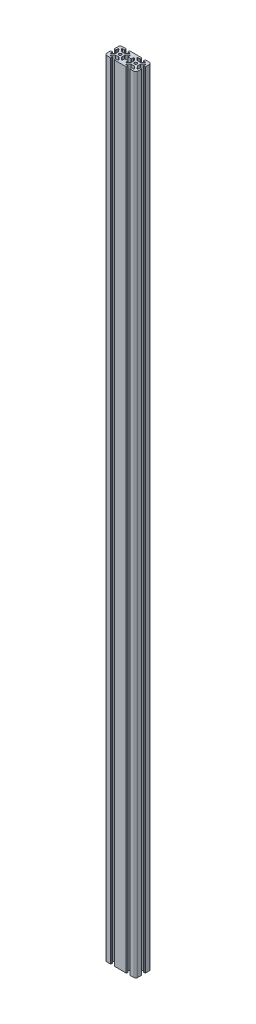
SolidWorks part; units mm, degrees
material "4032-T6"
ref_plane "Front Plane" through (0, 0, 0) normal (0, 0, 1) x (1, 0, 0)
ref_plane "Top Plane" through (0, 0, 0) normal (0, 1, 0) x (1, 0, 0)
ref_plane "Right Plane" through (0, 0, 0) normal (1, 0, 0) x (0, 0, -1)
sketch "Sketch1" plane through (0, 0, 0) normal (0, 1, 0) x (1, 0, 0)
  line L1 (5, 0) -> (75, 0)
  line L2 (0, -5) -> (0, -35)
  line L3 (5, -40) -> (75, -40)
  line L4 (80, -5) -> (80, -35)
  arc A0 (75, -40) -> (80, -35) centre (75, -35) ccw
  arc A1 (80, -5) -> (75, 0) centre (75, -5) ccw
  arc A2 (5, -40) -> (0, -35) centre (5, -35) cw
  arc A3 (0, -5) -> (5, 0) centre (5, -5) cw
  point P7 (80, -40)
  point P10 (80, 0)
  point P15 (0, 0)
  dimension "D3" = 5
  dimension "D1" = 80
  dimension "D2" = 40
extrude "Boss-Extrude1" add sketch "Sketch1" along normal blind 2016 contours L3 A0 L4 A1 L1 A3 L2 A2
sketch "Sketch3" plane through (0, 2016, 0) normal (0, 1, 0) x (1, 0, 0)
  line L0 (40, -2.5254) -> (40, -32.3671)
  line L1 (0, -5) -> (0, -35) construction
  line L2 (5, 0) -> (75, 0) construction
  circle A0 centre (20, -20) radius 3.4
  dimension "D4" = 6.8
  dimension "D1" = 40
  dimension "D2" = 20
  dimension "D3" = 20
extrude "Cut-Extrude1" cut sketch "Sketch3" against normal through all contours A0
ref_plane "mirro-plane" through (40, 0, 0) normal (1, 0, 0) x (0, 0, -1)
mirror "Mirror3" about plane through (40, 0, 0) normal (1, 0, 0) of "Cut-Extrude1"
ref_plane "sk5mirrorPlane" through (0, 0, 20) normal (0, 0, 1) x (1, 0, 0)
sketch "Sketch7" plane through (0, 0, 0) normal (0, -1, 0) x (-1, 0, 0)
  line L2 (-5, -40) -> (-75, -40) construction
  line L4 (-15.9, -40) -> (-24.1, -40)
  line L8 (-15.9, -40) -> (-15.9, -36.5)
  line L12 (-16.3092, -27.8) -> (-23.6908, -27.8)
  line L23 (-10.5103, -35.5) -> (-14.9, -35.5)
  line L25 (-24.1, -40) -> (-24.1, -36.5)
  line L27 (-15.6082, -28.0868) -> (-9.8093, -33.7868)
  line L31 (-29.4898, -35.5) -> (-25.1, -35.5)
  line L43 (-24.3918, -28.0868) -> (-30.1908, -33.7868)
  arc A0 (-24.3918, -28.0868) -> (-23.6908, -27.8) centre (-23.6908, -28.8) cw
  arc A1 (-16.3092, -27.8) -> (-15.6082, -28.0868) centre (-16.3092, -28.8) cw
  arc A2 (-30.1908, -33.7868) -> (-29.4898, -35.5) centre (-29.4898, -34.5) ccw
  arc A3 (-9.8093, -33.7868) -> (-10.5103, -35.5) centre (-10.5103, -34.5) cw
  arc A4 (-25.1, -35.5) -> (-24.1, -36.5) centre (-25.1, -36.5) cw
  arc A5 (-14.9, -35.5) -> (-15.9, -36.5) centre (-14.9, -36.5) ccw
  point P96 (-24.1, -35.5)
  dimension "D17" = 0
  dimension "D18" = 1
  dimension "D8" = 12.2
extrude "Cut-Extrude2" cut sketch "Sketch7" against normal through all
fillet "Fillet1" radius 1 2 edges at (15.9, 1008, 40) (24.1, 1008, 40)
mirror "Mirror8" about plane through (40, 0, 0) normal (1, 0, 0) of "Cut-Extrude2"
fillet "Fillet2" radius 1 1 edges at (55.9, 1008, 40)
fillet "Fillet3" radius 1 1 edges at (64.1, 1008, 40)
sketch "Sketch9" plane through (0, 0, 0) normal (0, 1, 0) x (1, 0, 0)
  line L1 (14.8998, -4.5007) -> (10.4505, -4.5007)
  line L3 (24.0998, -3.5) -> (24.1, 0)
  line L4 (15.8998, -3.5008) -> (15.9, 0)
  line L5 (15.9, 0) -> (24.1, 0)
  line L6 (16.1497, -12.2) -> (23.8503, -12.2)
  line L7 (5, 0) -> (75, 0) construction
  line L8 (25.0998, -4.5) -> (29.5503, -4.5)
  line L12 (9.7434, -6.2078) -> (15.4426, -11.9071)
  line L16 (24.5574, -11.9071) -> (30.2574, -6.2071)
  arc A0 (15.8998, -3.5008) -> (14.8998, -4.5007) centre (14.8998, -3.5007) cw
  arc A1 (24.0998, -3.5) -> (25.0998, -4.5) centre (25.0998, -3.5) ccw
  arc A2 (29.5503, -4.5) -> (30.2574, -6.2071) centre (29.5503, -5.5) cw
  arc A3 (24.5574, -11.9071) -> (23.8503, -12.2) centre (23.8503, -11.2) cw
  arc A4 (9.7434, -6.2078) -> (10.4505, -4.5007) centre (10.4505, -5.5007) cw
  arc A5 (15.4426, -11.9071) -> (16.1497, -12.2) centre (16.1497, -11.2) ccw
  dimension "D2" = 1
  dimension "D1" = 0
  dimension "D5" = 12.2
  dimension "D6" = 4.5
extrude "Cut-Extrude3" cut sketch "Sketch9" along normal through all
mirror "Mirror9" about plane through (40, 0, 0) normal (1, 0, 0) of "Cut-Extrude3"
sketch "Sketch10" plane through (0, 0, 0) normal (0, 1, 0) x (1, 0, 0)
  line L0 (4.5, -14.9) -> (4.5, -10.5861)
  line L4 (0, -24.1) -> (3.5, -24.1)
  line L5 (0, -15.9) -> (3.5, -15.9)
  line L8 (12.2, -23.4919) -> (12.2, -16.5081)
  line L10 (0, -5) -> (0, -35) construction
  line L13 (4.5, -29.4139) -> (4.5, -25.1)
  line L25 (11.9205, -24.1853) -> (6.2205, -30.1074)
  line L26 (11.9205, -15.8147) -> (6.2205, -9.8926)
  line L29 (0, -24.1) -> (0, -15.9)
  arc A0 (4.5, -14.9) -> (3.5, -15.9) centre (3.5, -14.9) cw
  arc A1 (3.5, -24.1) -> (4.5, -25.1) centre (3.5, -25.1) cw
  arc A2 (6.2205, -9.8926) -> (4.5, -10.5861) centre (5.5, -10.5861) ccw
  arc A3 (11.9205, -15.8147) -> (12.2, -16.5081) centre (11.2, -16.5081) cw
  arc A4 (11.9205, -24.1853) -> (12.2, -23.4919) centre (11.2, -23.4919) ccw
  arc A5 (4.5, -29.4139) -> (6.2205, -30.1074) centre (5.5, -29.4139) ccw
  dimension "D3" = 1
  dimension "D7" = 12.2
  dimension "D9" = 4.5
  dimension "D17" = 0
extrude "Cut-Extrude4" cut sketch "Sketch10" along normal through all
fillet "Fillet4" radius 1 1 edges at (24.1, 1008, 0)
fillet "Fillet5" radius 1 1 edges at (64.1, 1008, 0)
fillet "Fillet6" radius 1 1 edges at (55.9, 1008, 0)
fillet "Fillet7" radius 1 1 edges at (15.9, 1008, 0)
fillet "Fillet8" radius 1 1 edges at (0, 1008, 24.1)
fillet "Fillet9" radius 1 1 edges at (0, 1008, 15.9)
sketch "Sketch11" plane through (0, 0, 0) normal (0, 1, 0) x (1, 0, 0)
  line L0 (75.5, -29.6797) -> (75.5, -25.1)
  line L1 (80, -5) -> (80, -35) construction
  line L2 (67.5, -16.0953) -> (67.5, -23.9047)
  line L5 (75.5, -14.9) -> (75.5, -10.3203)
  line L7 (80, -24.1) -> (80, -15.9)
  line L8 (80, -5) -> (80, -35) construction
  line L13 (113.5168, -27.8) -> (113.5178, -27.6385)
  line L17 (67.8065, -15.3748) -> (73.8065, -9.5998)
  line L63 (67.8065, -24.6252) -> (73.8065, -30.4002)
  line L66 (76.5, -15.9) -> (80, -15.9)
  line L68 (76.5, -24.1) -> (80, -24.1)
  arc A44 (75.5, -25.1) -> (76.5, -24.1) centre (76.5, -25.1) cw
  arc A45 (75.5, -14.9) -> (76.5, -15.9) centre (76.5, -14.9) ccw
  arc A46 (73.8065, -9.5998) -> (75.5, -10.3203) centre (74.5, -10.3203) cw
  arc A47 (73.8065, -30.4002) -> (75.5, -29.6797) centre (74.5, -29.6797) ccw
  arc A48 (67.8065, -24.6252) -> (67.5, -23.9047) centre (68.5, -23.9047) cw
  arc A49 (67.8065, -15.3748) -> (67.5, -16.0953) centre (68.5, -16.0953) ccw
  dimension "D3" = 1
  dimension "D2" = 4.5
  dimension "D4" = 12.5
ref_plane "offset1" through (60, 0, 0) normal (1, 0, 0) x (0, 0, -1)
mirror "Mirror10" about plane through (40, 0, 0) normal (1, 0, 0) of "Cut-Extrude4"
fillet "Fillet10" radius 1 1 edges at (80, 1008, 15.9)
fillet "Fillet11" radius 1 1 edges at (80, 1008, 24.1)
mirror "Mirror11" about plane through (60, 0, 0) normal (1, 0, 0) of "Mirror10"
ref_plane "Plane2" through (20, 0, 0) normal (-1, 0, 0) x (0, 0, 1)
mirror "Mirror12" about plane through (20, 0, 0) normal (-1, 0, 0) of "Cut-Extrude4"
sketch "Sketch12" plane through (0, 0, 0) normal (0, -1, 0) x (-1, 0, 0)
  line L0 (-28.0795, -24.1853) -> (-39.3271, -35.8711)
  line L2 (-51.9226, -24.2109) -> (-40.7702, -35.8689)
  line L4 (-39.2795, -4.1783) -> (-28.0795, -15.8147)
  line L7 (-51.9205, -15.8147) -> (-40.7205, -4.1783)
  line L8 (-27.8, -23.4919) -> (-27.8, -16.5081)
  line L9 (-52.2, -23.5196) -> (-52.2, -16.5081)
  line L10 (-52.2, -23.4919) -> (-52.2, -16.5081) construction
  line L11 (-27.8, -23.4919) -> (-27.8, -16.5081) construction
  arc A0 (-39.2795, -4.1783) -> (-40.7205, -4.1783) centre (-40, -4.8718) ccw
  arc A1 (-39.3271, -35.8711) -> (-40.7702, -35.8689) centre (-40.0476, -35.1776) cw
  arc A2 (-51.9205, -15.8147) -> (-52.2, -16.5081) centre (-51.2, -16.5081) ccw
  arc A3 (-52.2, -23.5196) -> (-51.9226, -24.2109) centre (-51.2, -23.5196) ccw
  arc A4 (-28.0795, -15.8147) -> (-27.8, -16.5081) centre (-28.8, -16.5081) cw
  arc A5 (-27.8, -23.4919) -> (-28.0795, -24.1853) centre (-28.8, -23.4919) cw
  dimension "D3" = 1
  dimension "D4" = 1
  dimension "D1" = 0
  dimension "D2" = 0
extrude "Cut-Extrude5" cut sketch "Sketch12" against normal blind 1000
